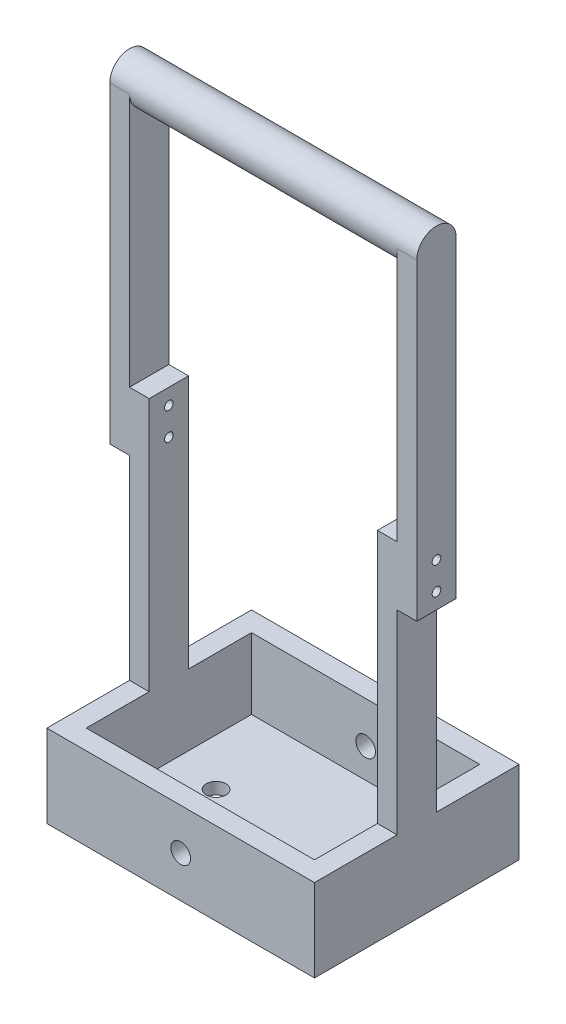
SolidWorks part; units mm, degrees
ref_plane "前视基准面" through (0, 0, 0) normal (0, 0, 1) x (1, 0, 0)
ref_plane "上视基准面" through (0, 0, 0) normal (0, 1, 0) x (1, 0, 0)
ref_plane "右视基准面" through (0, 0, 0) normal (1, 0, 0) x (0, 0, -1)
sketch "草图1" plane through (0, 0, 0) normal (0, 1, 0) x (1, 0, 0)
  line L1 (-68, 52) -> (68, 52)
  line L2 (-68, 52) -> (-68, -52)
  line L3 (-68, -52) -> (68, -52)
  line L4 (68, 52) -> (68, -52)
  line L5 (-68, 52) -> (68, -52) construction
  line L6 (-68, -52) -> (68, 52) construction
  point P0 (0, 0)
  dimension "D1" = 136
  dimension "D2" = 104
extrude "凸台-拉伸1" add sketch "草图1" along normal blind 42
sketch "草图2" plane through (0, 42, 0) normal (0, 1, 0) x (1, 0, 0)
  line L1 (-58, 42) -> (58, 42)
  line L2 (-58, 42) -> (-58, -42)
  line L3 (-58, -42) -> (58, -42)
  line L4 (58, 42) -> (58, -42)
  line L5 (-58, 42) -> (58, -42) construction
  line L6 (-58, -42) -> (58, 42) construction
  point P0 (0, 0)
  dimension "D1" = 116
  dimension "D2" = 84
extrude "切除-拉伸1" cut sketch "草图2" against normal blind 36
sketch "草图3" plane through (0, 6, 0) normal (0, 1, 0) x (1, 0, 0)
  line L0 (-70.8007, 0) -> (69.7878, 0) construction
  line L1 (0, 53.9361) -> (0, -53.3284) construction
  line L2 (-34, 53.9361) -> (-34, -53.3284) construction
  line L3 (34, 53.9361) -> (34, -53.3284) construction
  line L5 (-70.8007, 26) -> (69.7878, 26) construction
  line L6 (-70.8007, -26) -> (69.7878, -26) construction
  circle A6 centre (-34, 0) radius 5
  circle A8 centre (34, 0) radius 5
  dimension "D10" = 10
  dimension "D12" = 10
  dimension "D1" = 34
  dimension "D2" = 34
  dimension "D3" = 26
  dimension "D4" = 26
extrude "切除-拉伸2" cut sketch "草图3" against normal up to next
sketch "草图5" plane through (0, 0, 52) normal (0, 0, 1) x (1, 0, 0)
  line L0 (-68, 21) -> (68, 21) construction
  line L1 (-68, 42) -> (-68, 0) construction
  line L2 (68, 42) -> (68, 0) construction
  line L3 (0, 0) -> (0, 42) construction
  line L4 (-68, 0) -> (68, 0) construction
  line L5 (-68, 42) -> (68, 42) construction
  circle A2 centre (0, 21) radius 5
  dimension "D5" = 10
extrude "切除-拉伸4" cut sketch "草图5" against normal blind 104
sketch "草图6" plane through (0, 42, 0) normal (0, 1, 0) x (1, 0, 0)
  line L0 (-68, 0) -> (68, 0) construction
  line L1 (-68, 52) -> (-68, -52) construction
  line L2 (68, -52) -> (68, 52) construction
  line L3 (0, 52) -> (0, -52) construction
  line L4 (68, 52) -> (-68, 52) construction
  line L5 (-68, -52) -> (68, -52) construction
  line L6 (-58, 42) -> (-58, -42) construction
  line L7 (-68, 10) -> (-58, 10)
  line L8 (-68, 10) -> (-68, -10)
  line L9 (-68, -10) -> (-58, -10)
  line L10 (-58, 10) -> (-58, -10)
  line L12 (68, -10) -> (58, -10)
  line L13 (58, 10) -> (58, -10)
  line L14 (68, 10) -> (58, 10)
  line L15 (68, 10) -> (68, -10)
  dimension "D1" = 20
  dimension "D2" = 10
extrude "凸台-拉伸2" add sketch "草图6" along normal blind 258
sketch "草图8" plane through (-68, 0, 0) normal (-1, 0, 0) x (0, 0, 1)
  line L0 (-91.8023, 171) -> (107.0528, 171) construction
  line L1 (-52, 42) -> (-10, 42) construction
  line L2 (-10, 300) -> (-10, 42) construction
  line L3 (-10, 171) -> (10, 171)
  line L4 (-10, 171) -> (-10, 141)
  line L5 (-10, 141) -> (10, 141)
  line L6 (10, 171) -> (10, 141)
  line L7 (10, 300) -> (10, 42) construction
  dimension "D1" = 129
  dimension "D2" = 30
extrude "凸台-拉伸4" add sketch "草图8" along normal blind 10
sketch "草图9" plane through (0, 171, 0) normal (0, 1, 0) x (1, 0, 0)
  line L0 (-68, -10) -> (-68, -52) construction
  line L1 (-78, 10) -> (-68, 10)
  line L2 (-78, 10) -> (-78, -10)
  line L3 (-78, -10) -> (-68, -10)
  line L4 (-68, 10) -> (-68, -10)
  line L5 (-78, -10) -> (-68, -10) construction
extrude "凸台-拉伸5" add sketch "草图9" along normal blind 129
sketch "草图10" plane through (68, 0, 0) normal (1, 0, 0) x (0, 0, -1)
  line L0 (-82.4745, 171) -> (103.8889, 171) construction
  line L1 (-52, 42) -> (-10, 42) construction
  line L7 (10, 300) -> (10, 42) construction
  line L11 (10, 171) -> (10, 141)
  line L12 (10, 171) -> (-10, 171)
  line L13 (-10, 300) -> (-10, 42) construction
  line L14 (-10, 171) -> (-10, 141)
  line L15 (-10, 141) -> (10, 141)
  dimension "D1" = 129
  dimension "D2" = 30
extrude "凸台-拉伸6" add sketch "草图10" along normal blind 10
sketch "草图12" plane through (0, 171, 0) normal (0, 1, 0) x (1, 0, 0)
  line L1 (68, 10) -> (78, 10)
  line L2 (68, 10) -> (68, -10)
  line L3 (68, -10) -> (78, -10)
  line L4 (78, 10) -> (78, -10)
extrude "凸台-拉伸8" add sketch "草图12" along normal blind 129
sketch "草图13" plane through (-58, 0, 0) normal (1, 0, 0) x (0, 0, -1)
  line L0 (10, 300) -> (10, 42) construction
  line L5 (-10, 300) -> (10, 300)
  line L6 (-10, 300) -> (-10, 171)
  line L7 (-10, 171) -> (10, 171)
  line L8 (10, 300) -> (10, 171)
  dimension "D1" = 129
extrude "切除-拉伸5" cut sketch "草图13" against normal blind 10
sketch "草图14" plane through (58, 0, 0) normal (-1, 0, 0) x (0, 0, 1)
  line L0 (10, 141) -> (10, 300) construction
  line L1 (-10, 300) -> (10, 300)
  line L2 (-10, 300) -> (-10, 171)
  line L3 (-10, 171) -> (10, 171)
  line L4 (10, 300) -> (10, 171)
  dimension "D1" = 129
extrude "切除-拉伸6" cut sketch "草图14" against normal blind 10
sketch "草图15" plane through (-78, 0, 0) normal (-1, 0, 0) x (0, 0, 1)
  line L0 (-10, 300) -> (10, 300) construction
  circle A0 centre (0, 300) radius 10
extrude "凸台-拉伸9" add sketch "草图15" against normal blind 156
sketch "草图16" plane through (-58, 0, 0) normal (1, 0, 0) x (0, 0, -1)
  line L0 (0, 205.6983) -> (0, 82.2496) construction
  line L1 (-10, 171) -> (10, 171) construction
  circle A0 centre (0, 163) radius 2.2
  circle A1 centre (0, 149) radius 2.2
  dimension "D1" = 4.4
  dimension "D2" = 4.4
  dimension "D3" = 8
  dimension "D4" = 14
extrude "切除-拉伸7" cut sketch "草图16" against normal up to next and the other way blind 136
